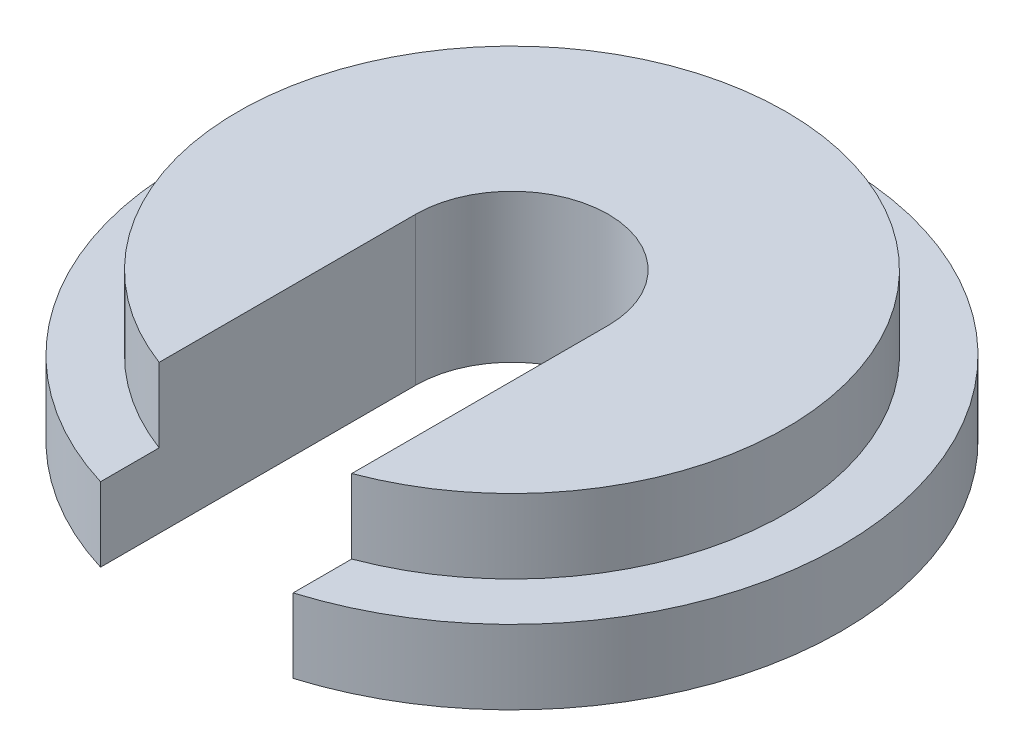
SolidWorks part; units mm, degrees
ref_plane "Front Plane" through (0, 0, 0) normal (0, 0, 1) x (1, 0, 0)
ref_plane "Top Plane" through (0, 0, 0) normal (0, 1, 0) x (1, 0, 0)
ref_plane "Right Plane" through (0, 0, 0) normal (1, 0, 0) x (0, 0, -1)
sketch "Sketch1" plane through (0, 0, 0) normal (0, 1, 0) x (1, 0, 0)
  circle A0 centre (0, 0) radius 44.5
extrude "Boss-Extrude1" add sketch "Sketch1" along normal blind 10
sketch "Sketch2" plane through (0, 10, 0) normal (0, 1, 0) x (1, 0, 0)
  circle A0 centre (0, 0) radius 37
extrude "Boss-Extrude2" add sketch "Sketch2" along normal blind 10
sketch "Sketch3" plane through (0, 0, 0) normal (0, -1, 0) x (1, 0, 0)
  line L0 (-13, 0) -> (-13, 42.5588)
  line L1 (-13, 42.5588) -> (-13, 62.2171)
  line L2 (-13, 62.2171) -> (13, 62.2171)
  line L3 (13, 62.2171) -> (13, 0)
  arc A0 (-13, 0) -> (13, 0) centre (0, 0) ccw
  circle A1 centre (0, 0) radius 44.5 construction
extrude "Cut-Extrude1" cut sketch "Sketch3" against normal through all
